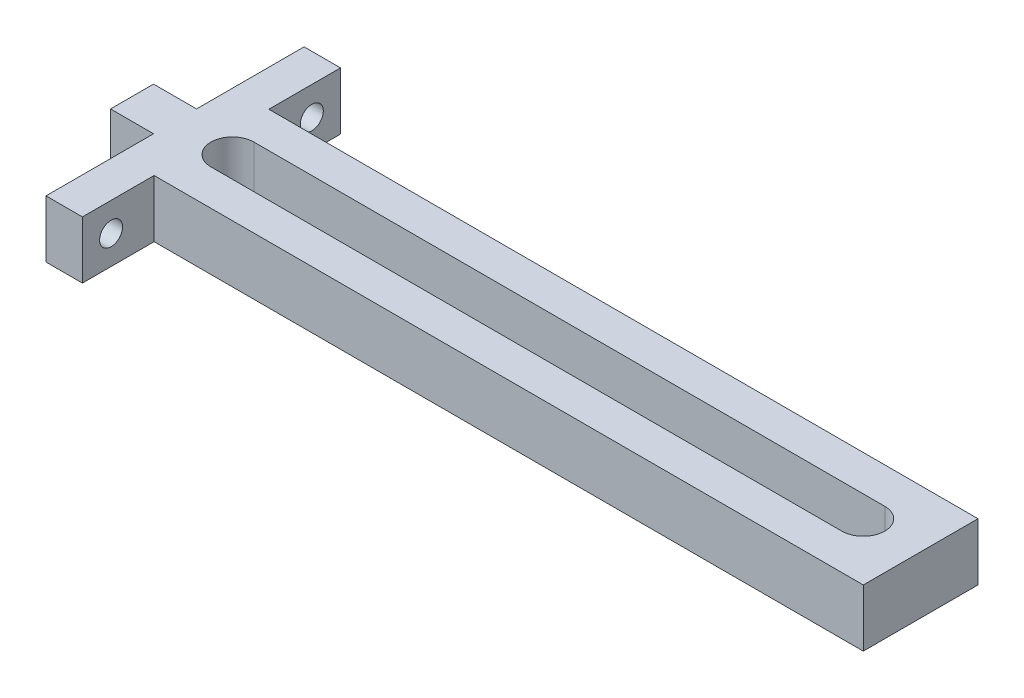
SolidWorks part; units mm, degrees
material "Aleación 1060"
ref_plane "Alzado" through (0, 0, 0) normal (0, 0, 1) x (1, 0, 0)
ref_plane "Planta" through (0, 0, 0) normal (0, 1, 0) x (1, 0, 0)
ref_plane "Vista lateral" through (0, 0, 0) normal (1, 0, 0) x (0, 0, -1)
sketch "Croquis1" plane through (0, 0, 0) normal (0, 1, 0) x (1, 0, 0)
  line L0 (110, 0) -> (-110, 0) construction
  line L1 (130, -20) -> (-130, -20)
  line L2 (130, -20) -> (130, 20)
  line L3 (130, 20) -> (-130, 20)
  line L4 (-130, -20) -> (-130, 20)
  line L5 (130, -20) -> (-130, 20) construction
  line L6 (130, 20) -> (-130, -20) construction
  line L8 (110, -7.5) -> (-110, -7.5)
  line L9 (110, 7.5) -> (-110, 7.5)
  line L10 (-115, -15) -> (-145, -15) construction
  line L11 (-115, -15) -> (-115, 15) construction
  line L12 (-115, 15) -> (-145, 15) construction
  line L13 (-145, -15) -> (-145, 15) construction
  line L14 (-115, -15) -> (-145, 15) construction
  line L15 (-115, 15) -> (-145, -15) construction
  line L16 (-145, 7.5) -> (-115, 7.5) construction
  line L17 (-145, 7.5) -> (-145, -7.5) construction
  line L18 (-145, -7.5) -> (-115, -7.5) construction
  line L19 (-115, 7.5) -> (-115, -7.5) construction
  line L20 (-145, 7.5) -> (-115, -7.5) construction
  line L21 (-145, -7.5) -> (-115, 7.5) construction
  line L22 (-130, -7.5) -> (-145, -7.5)
  line L23 (-130, -7.5) -> (-130, 7.5)
  line L24 (-130, 7.5) -> (-145, 7.5)
  line L25 (-145, -7.5) -> (-145, 7.5)
  line L26 (-130, 15) -> (-117.3, 15)
  line L27 (-130, 15) -> (-130, 45)
  line L28 (-130, 45) -> (-117.3, 45)
  line L29 (-117.3, 15) -> (-117.3, 45)
  line L30 (-130, -15) -> (-117.3, -15)
  line L31 (-130, -15) -> (-130, -45)
  line L32 (-130, -45) -> (-117.3, -45)
  line L33 (-117.3, -15) -> (-117.3, -45)
  line L34 (-145, -7.5) -> (-130, -7.5)
  line L35 (-145, -7.5) -> (-145, 7.5)
  line L36 (-145, 7.5) -> (-130, 7.5)
  line L37 (-130, -7.5) -> (-130, 7.5)
  arc A0 (110, -7.5) -> (110, 7.5) centre (110, 0) ccw
  arc A1 (-110, 7.5) -> (-110, -7.5) centre (-110, 0) ccw
  point P0 (0, 0)
  point P8 (-130, 0)
  point P10 (0, 0)
  point P18 (-130, 0)
  dimension "D3" = 7.5
  dimension "D1" = 40
  dimension "D2" = 260
  dimension "D4" = 30
  dimension "D5" = 15
  dimension "D6" = 30
  dimension "D7" = 15
  dimension "D8" = 30
  dimension "D9" = 12.7
  dimension "D10" = 30
  dimension "D11" = 12.7
  dimension "D12" = 15
  dimension "D14" = 220
extrude "Saliente-Extruir1" add sketch "Croquis1" along normal blind 20 contours L30 L33 L1 L2 L3 L29 L26 L4 A1 L9 A0 L8 | L33 L1 L31 L32 | L33 L30 L4 L1 | L26 L29 L3 L4 | L3 L29 L28 L27 | L25 L22 L4 L24
sketch "Croquis2" plane through (-130, 0, 0) normal (-1, 0, 0) x (0, 0, 1)
  line L1 (-45, 20) -> (-45, 0) construction
  circle A0 centre (-35, 10) radius 4
  circle A1 centre (35, 10) radius 4
  dimension "D1" = 70
  dimension "D2" = 10
extrude "Cortar-Extruir1" cut sketch "Croquis2" against normal blind 12.7
